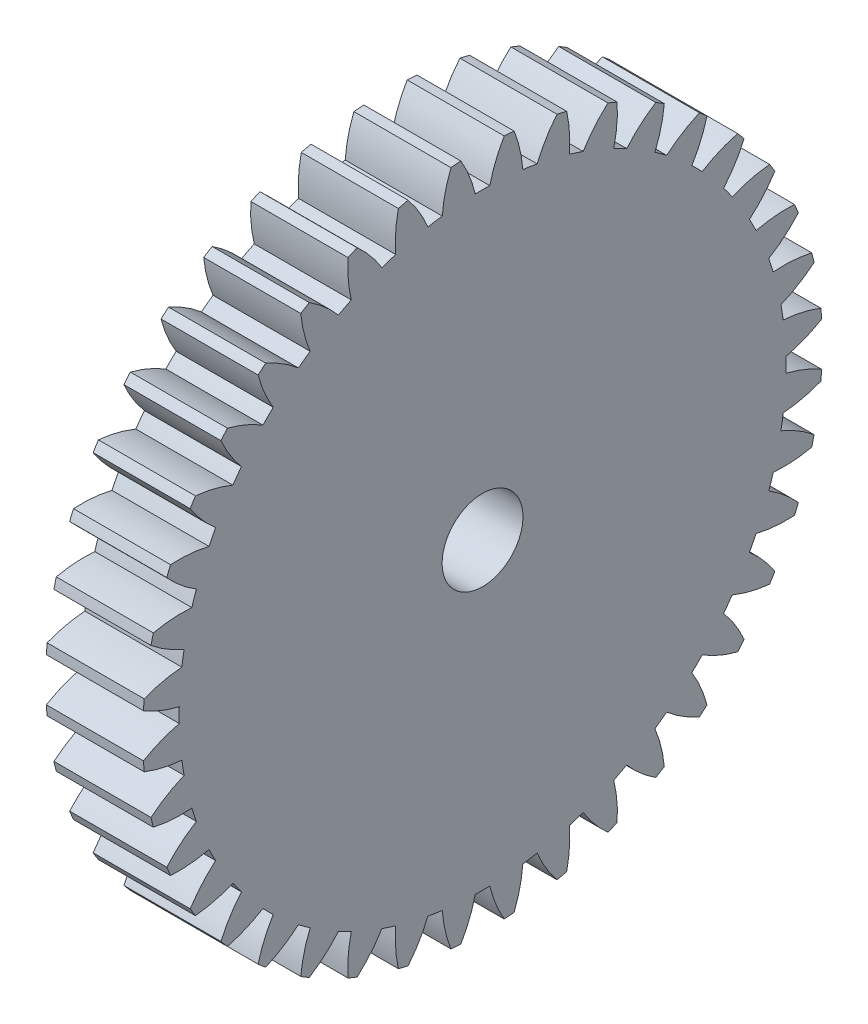
SolidWorks part; units mm, degrees
ref_plane "Plane1" through (0, 0, 0) normal (0, 0, 1) x (1, 0, 0)
ref_plane "Plane2" through (0, 0, 0) normal (0, 1, 0) x (1, 0, 0)
ref_plane "Plane3" through (0, 0, 0) normal (1, 0, 0) x (0, 0, -1)
other "Configuration Table"
sketch "HoldingSke" plane through (0, 0, 0) normal (0, 1, 0) x (1, 0, 0)
  line L0 (0, 0) -> (0.766, -0.6428)
  line L1 (-15, 0) -> (100, 0) construction
  line L2 (0, 0) -> (-2.1039, 2.3779)
  line L3 (0, 0) -> (-11.863, 4.5341)
  line L4 (0, 0) -> (6.6156, 5.5511)
  line L5 (0, 0) -> (-46.8476, -17.4728)
  line L6 (0, 0) -> (-4.9738, -3.3558)
  line L7 (-2.1039, 2.3779) -> (8.6586, 51.2059)
  line L8 (-76.2, 54.61) -> (-75.3, 54.61)
  line L9 (-71.009, 38.7566) -> (-53.1078, 45.2721)
  line L10 (-76.2, 71.12) -> (104.1128, 71.12)
  line L11 (0, 0) -> (-6, 0)
  line L12 (-76.2, 101.6) -> (-76.162, 101.6)
  line L13 (24.9733, 27.94) -> (52.9518, 28.4284)
  line L14 (24.9733, 27.94) -> (24.9743, 27.94)
  line L15 (24.9733, 27.94) -> (100.4006, 29.5858)
  line L16 (-63.627, -1) -> (-12.827, -1)
  circle A0 centre (0, 0) radius 2.5
  circle A1 centre (0, 0) radius 18.749
  circle A2 centre (0, 0) radius 37.5
  circle A3 centre (0, 0) radius 2.5
  dimension "MHD" = 37.498
  dimension "Hub_dia" = 75
  dimension "Bore" = 5
  dimension "MBD" = 5
  dimension "Num_teeth" = 40
  dimension "Pitch" = 1
  dimension "Overall_len" = 50
  dimension "Show_teeth" = 40
  dimension "Thickness" = 6
  dimension "OAL" = 50.0001
  dimension "T_dim" = 0.9
  dimension "Ap" = 20
  dimension "H" = 19.05
  dimension "Pitch_radius" = 180.3128
  dimension "Width" = 6
  dimension "Backlash" = 0.038
  dimension "Addendum_fac" = 1
  dimension "Dedendum_fac" = 1.25
  dimension "Clearance_fac" = 0.25
  dimension "Dedendum_add" = 0.001
  dimension "Module" = 1
sketch "BasProSke" plane through (0, 0, 0) normal (0, 1, 0) x (1, 0, 0)
  line L0 (-10, 0) -> (60, 0) construction
  line L1 (0, 0) -> (0, 21)
  line L2 (0, 0) -> (6, 0)
  line L3 (6, 0) -> (6, 21)
  line L4 (6, 21) -> (0, 21)
  dimension "Thickness" = 6
  dimension "Diameter" = 42
revolve "Base-Revolve" add sketch "BasProSke" angle 360 about L0
sketch "TooCutSke" plane through (0, 0, 0) normal (1, 0, 0) x (0, 0, -1)
  line L1 (0, 0) -> (0, 107) construction
  line L2 (0, 0) -> (-0.8517, 19.9819) construction
  line L3 (0, 0) -> (-3.1363, 39.8509) construction
  line L4 (-0.8517, 19.9819) -> (-1.5682, 19.9255) construction
  arc A0 (0.4487, 18.7436) -> (-0.4487, 18.7436) centre (0, 0) ccw
  arc A1 (1.3547, 20.9817) -> (-1.3547, 20.9817) centre (0, 0) ccw
  circle A2 centre (0, 0) radius 20 construction
  circle A3 centre (0, 0) radius 18.7939 construction
  arc A4 (-0.4487, 18.7436) -> (-1.3547, 20.9817) centre (-8.2322, 16.895) ccw
  arc A5 (1.3547, 20.9817) -> (0.4487, 18.7436) centre (8.2322, 16.895) ccw
  dimension "Root_dia" = 37.498
  dimension "Overcut_dia" = 42.0508
  dimension "Pitch_dia" = 40
  dimension "Base_dia" = 37.5877
  dimension "Flank_rad" = 8
  dimension "Half_ang" = 4.5
  dimension "Half_CT" = 0.7187
extrude "ToothCut" cut sketch "TooCutSke" along normal through all
fillet "Breaks" [suppressed] radius 0.02
fillet "RootFillets" [suppressed] radius 0.251
pattern_circular "TeethCuts" count 40 every 9 about axis through (-10, 0, 0) along (1, 0, 0) of "ToothCut", "RootFillets", "Breaks"
sketch "HubNeaOneSke" plane through (0, 0, 0) normal (-1, 0, 0) x (0, 0, 1)
  circle A0 centre (0, 0) radius 18.749
  dimension "Diameter" = 37.498
extrude "HubNearOne" [suppressed] add sketch "HubNeaOneSke" along normal blind 44.0001
sketch "HubNeaBotSke" plane through (0, 0, 0) normal (-1, 0, 0) x (0, 0, 1)
  circle A0 centre (0, 0) radius 18.749
  dimension "Diameter" = 37.498
extrude "HubNearBoth" [suppressed] add sketch "HubNeaBotSke" along normal blind 22
ref_plane "FarPln" through (6, 0, 0) normal (1, 0, 0) x (0, 0, -1)
sketch "HubFarSke" plane through (6, 0, 0) normal (1, 0, 0) x (0, 0, -1)
  circle A0 centre (0, 0) radius 18.749
  dimension "Diameter" = 37.498
extrude "HubFar" [suppressed] add sketch "HubFarSke" along normal blind 22
sketch "BorSke" plane through (0, 0, 0) normal (1, 0, 0) x (0, 0, -1)
  circle A0 centre (0, 0) radius 2.5
  dimension "Diameter" = 5
extrude "Bore" cut sketch "BorSke" along normal mid plane 100.0001
sketch "KeySke" plane through (0, 0, 0) normal (1, 0, 0) x (0, 0, -1)
  line L0 (-1, 0) -> (-1, 3.4)
  line L1 (-1, 3.4) -> (1, 3.4)
  line L2 (1, 3.4) -> (1, 0)
  line L3 (0, 0) -> (0, 34) construction
  line L4 (-1, 0) -> (1, 0)
  dimension "Offset" = 3.4
  dimension "Width" = 2
extrude "Keyway" [suppressed] cut sketch "KeySke" along normal mid plane 100.0001
pattern_circular "Keyway2" [suppressed] count 2 every 90 about axis through (-10, 0, 0) along (1, 0, 0)
equation "' \"Module@HoldingSke\" = 6.35"
equation "' \"Num_teeth@HoldingSke\" = 12"
equation "' \"Ap@HoldingSke\" =  20"
equation "' \"Ap@HoldingSke\" = 20"
equation "' \"Width@HoldingSke\" = 0.5 * 25.4"
equation "' \"Hub_dia@HoldingSke\"= 1 * 25.4"
equation "' \"Hub_dia@HoldingSke\" = 1 * 25.4"
equation "' \"Overall_len@HoldingSke\" = 1.0 * 25.4"
equation "' \"Bore@HoldingSke\" = 0.75 * 25.4"
equation "' \"T_dim@HoldingSke\" = 0.1 * 25.4"
equation "' \"Width@KeySke\" = 0.25 * 25.4"
equation "' \"Show_teeth@HoldingSke\" = 13"
equation "' \"Backlash@HoldingSke\" = 0.009 * 25.4"
equation "' \"Addendum_fac@HoldingSke\" = 1.0"
equation "' \"Dedendum_fac@HoldingSke\" = 1.25"
equation "' \"Dedendum_add@HoldingSke\" = 0.00005 * 25.4"
equation "' \"Clearance_fac@HoldingSke\" = 0.25"
equation "\"Pitch@HoldingSke\" = 1 / \"Module@HoldingSke\""
equation "\"Overcut_dia@TooCutSke\" = (\"Num_teeth@HoldingSke\" + 2 * \"Addendum_fac@HoldingSke\") / \"Pitch@HoldingSke\" + 0.002 * 25.4"
equation "\"Pitch_dia@TooCutSke\" = \"Num_teeth@HoldingSke\" / \"Pitch@HoldingSke\""
equation "\"Base_dia@TooCutSke\" = \"Num_teeth@HoldingSke\" / \"Pitch@HoldingSke\" * cos((\"Ap@HoldingSke\"  * 3.14159265 / 180))"
equation "\"Root_dia@TooCutSke\" = (\"Num_teeth@HoldingSke\" + 2) / \"Pitch@HoldingSke\" - 2 * (\"Addendum_fac@HoldingSke\" + \"Dedendum_fac@HoldingSke\") / \"Pitch@HoldingSke\" - \"Dedendum_add@HoldingSke\" * 2"
equation "\"Half_ang@TooCutSke\" = 180 / \"Num_teeth@HoldingSke\""
equation "\"Half_CT@TooCutSke\" = \"Num_teeth@HoldingSke\" / \"Pitch@HoldingSke\" * sin((3.14159265 / 2 / \"Num_teeth@HoldingSke\")) / 2 - 7 * \"Backlash@HoldingSke\" / 4"
equation "\"Flank_rad@TooCutSke\" = \"Num_teeth@HoldingSke\" / \"Pitch@HoldingSke\" / 5"
equation "\"Radius@RootFillets\" = \"Clearance_fac@HoldingSke\" / \"Pitch@HoldingSke\" + \"Dedendum_add@HoldingSke\""
equation "\"Break_rad@Breaks\" = 0.02 / \"Pitch@HoldingSke\""
equation "\"Thickness@HoldingSke\" = \"Width@HoldingSke\""
equation "\"OAL@HoldingSke\" = \"Thickness@HoldingSke\""
equation "\"MHD@HoldingSke\" = (\"Num_teeth@HoldingSke\" + 2) / \"Pitch@HoldingSke\" - 2 * (\"Addendum_fac@HoldingSke\" + \"Dedendum_fac@HoldingSke\")  / \"Pitch@HoldingSke\" - \"Dedendum_add@HoldingSke\" * 2"
equation "\"MBD@HoldingSke\" = (\"Num_teeth@HoldingSke\" + 2) / \"Pitch@HoldingSke\" - 2 * (\"Addendum_fac@HoldingSke\" + \"Dedendum_fac@HoldingSke\")  / \"Pitch@HoldingSke\" - \"Dedendum_add@HoldingSke\" * 2 - 0.002 * 25.4"
equation "\"MHD@HoldingSke\" = ((sgn( \"MHD@HoldingSke\" - \"Hub_dia@HoldingSke\" )-1)*( \"MHD@HoldingSke\" - \"Hub_dia@HoldingSke\" ))/-2+ \"Hub_dia@HoldingSke\""
equation "\"MBD@HoldingSke\" = ((sgn( \"MBD@HoldingSke\" - \"Bore@HoldingSke\" )-1)*( \"MBD@HoldingSke\" - \"Bore@HoldingSke\" ))/-2+ \"Bore@HoldingSke\""
equation "\"OAL@HoldingSke\" = ((sgn( \"OAL@HoldingSke\" - \"Overall_len@HoldingSke\" )+1)*( \"OAL@HoldingSke\" - \"Overall_len@HoldingSke\" ))/2 + \"Overall_len@HoldingSke\" + 0.000002 * 25.4"
equation "\"Num_teeth@TeethCuts\" = int( \"Show_teeth@HoldingSke\" ) + 1"
equation "\"Num_teeth@TeethCuts\" = ((sgn( \"Num_teeth@TeethCuts\" - \"Num_teeth@HoldingSke\" )-1)*( \"Num_teeth@TeethCuts\" - \"Num_teeth@HoldingSke\" ))/-2+ \"Num_teeth@HoldingSke\""
equation "\"Num_teeth@TeethCuts\" = ((sgn( \"Num_teeth@TeethCuts\" - 2.0)+1)*( \"Num_teeth@TeethCuts\" - 2.0))/2 +2.0"
equation "\"Angle@TeethCuts\" = 360.0 / \"Num_teeth@HoldingSke\""
equation "\"Diameter@BasProSke\" = (\"Num_teeth@HoldingSke\" + 2 * \"Addendum_fac@HoldingSke\") / \"Pitch@HoldingSke\""
equation "\"Thickness@BasProSke\"  = \"Thickness@HoldingSke\""
equation "' \"Fillet_rad@BasProSke\" =  \"Thickness@HoldingSke\" * 0.05"
equation "' \"Fillet_rad@BasProSke\" = \"Thickness@HoldingSke\" * 0.05"
equation "\"MHD@HoldingSke\" = ((sgn( \"MHD@HoldingSke\" - \"Root_dia@TooCutSke\" )-1)*( \"MHD@HoldingSke\" - \"Root_dia@TooCutSke\" ))/-2+ \"Root_dia@TooCutSke\""
equation "\"Diameter@HubNeaOneSke\" = \"MHD@HoldingSke\""
equation "\"Length@HubNearOne\" = \"OAL@HoldingSke\" - \"Thickness@BasProSke\""
equation "\"Diameter@HubNeaBotSke\" = \"MHD@HoldingSke\""
equation "\"Length@HubNearBoth\" = ( \"OAL@HoldingSke\" - \"Thickness@BasProSke\" ) / 2.0"
equation "\"Thickness@FarPln\" = \"Thickness@BasProSke\""
equation "\"Diameter@HubFarSke\" = \"MHD@HoldingSke\""
equation "\"Length@HubFar\" = ( \"OAL@HoldingSke\" - \"Thickness@BasProSke\" ) / 2.0"
equation "\"Diameter@BorSke\" = \"MBD@HoldingSke\""
equation "\"D1@Bore\" = \"OAL@HoldingSke\" * 2.0"
equation "\"D1@Keyway\" = \"OAL@HoldingSke\" * 2.0"
equation "\"Offset@KeySke\" = \"T_dim@HoldingSke\" + \"MBD@HoldingSke\" / 2.0"
